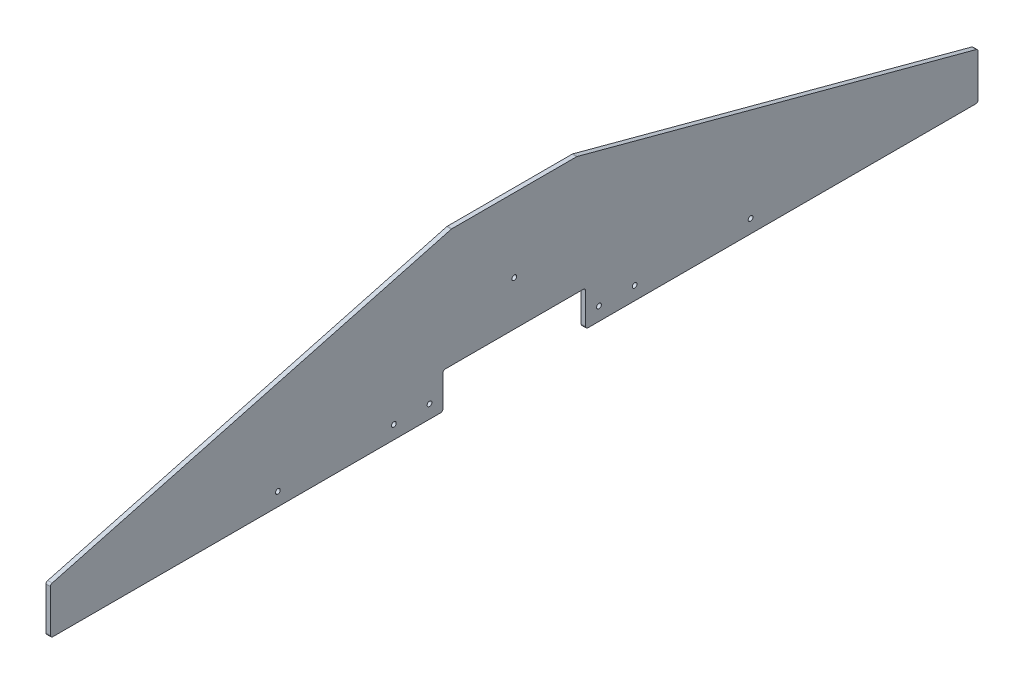
SolidWorks part; units mm, degrees
material "PC High Viscosity"
ref_plane "Front Plane" through (0, 0, 0) normal (0, 0, 1) x (1, 0, 0)
ref_plane "Top Plane" through (0, 0, 0) normal (0, 1, 0) x (1, 0, 0)
ref_plane "Right Plane" through (0, 0, 0) normal (1, 0, 0) x (0, 0, -1)
sketch "Sketch1" plane through (0, 0, 0) normal (1, 0, 0) x (0, 0, -1)
  line L0 (0, 0) -> (0, 219.075) construction
  line L1 (89.2656, 219.075) -> (-89.2656, 219.075)
  line L2 (-89.2656, 219.075) -> (-660.4, 66.04)
  line L3 (-660.4, 66.04) -> (-660.4, 0)
  line L4 (-660.4, 0) -> (660.4, 0)
  line L5 (660.4, 66.04) -> (660.4, 0)
  line L6 (89.2656, 219.075) -> (660.4, 66.04)
  dimension "D1" = 660.4
  dimension "D2" = 66.04
  dimension "D3" = 105
  dimension "D4" = 219.075
extrude "Boss-Extrude1" add sketch "Sketch1" along normal blind 6.35
sketch "Sketch2" plane through (6.35, 0, 0) normal (1, 0, 0) x (0, 0, -1)
  line L0 (-101.6, 0) -> (-101.6, 50.8)
  line L1 (-660.4, 0) -> (660.4, 0) construction
  line L2 (-101.6, 50.8) -> (101.6, 50.8)
  line L3 (101.6, 50.8) -> (101.6, 0)
  line L4 (101.6, 0) -> (-101.6, 0)
  line L5 (0, 0) -> (0, 50.8) construction
  dimension "D1" = 203.2
  dimension "D2" = 50.8
extrude "Cut-Extrude1" cut sketch "Sketch2" against normal through all
hole_wizard "1/4 Clearance Hole1" positions "Sketch3" profile "Sketch4" hole size "1/4" standard "ANSI Inch" end condition through all
sketch "Sketch3" plane through (0, 0, 0) normal (-1, 0, 0) x (0, 0, 1)
  line L0 (0, 0) -> (0, 219.075) construction
  line L1 (-89.2656, 219.075) -> (89.2656, 219.075) construction
  line L2 (-101.6, 0) -> (-101.6, 50.8) construction
  line L3 (-101.6, 0) -> (-660.4, 0) construction
  point P2 (-336.55, 19.05)
  point P4 (-120.65, 19.05)
  point P13 (120.65, 19.05)
  point P14 (336.55, 19.05)
  point P30 (0, 114.3)
  point P57 (-171.45, 19.05)
  point P63 (171.45, 19.05)
  dimension "D1" = 19.05
  dimension "D2" = 234.95
  dimension "D3" = 114.3
  dimension "D5" = 19.05
  dimension "D6" = 69.85
sketch "Sketch4" plane through (0, 19.05, -336.55) normal (0, 1, 0) x (0, 0, 1)
  line L0 (0, 0) -> (0, 6.35)
  line L1 (0, 6.35) -> (3.3782, 6.35)
  line L2 (3.3782, 6.35) -> (3.3782, 0)
  line L5 (3.3782, 0) -> (0, 0)
  line L11 (0, -6.35) -> (0, 107.95) construction
  dimension "Thru Hole Dia." = 6.7564
  dimension "Thru Hole Depth" = 6.35
fillet "Fillet1" radius 3.302 10 edges at (3.175, 50.8, -101.6) (3.175, 219.075, -89.2656) (3.175, 219.075, 89.2656) (3.175, 66.04, 660.4) (3.175, 0, 660.4) (3.175, 0, 101.6) (3.175, 50.8, 101.6) (3.175, 0, -101.6) (3.175, 66.04, -660.4) (3.175, 0, -660.4)
